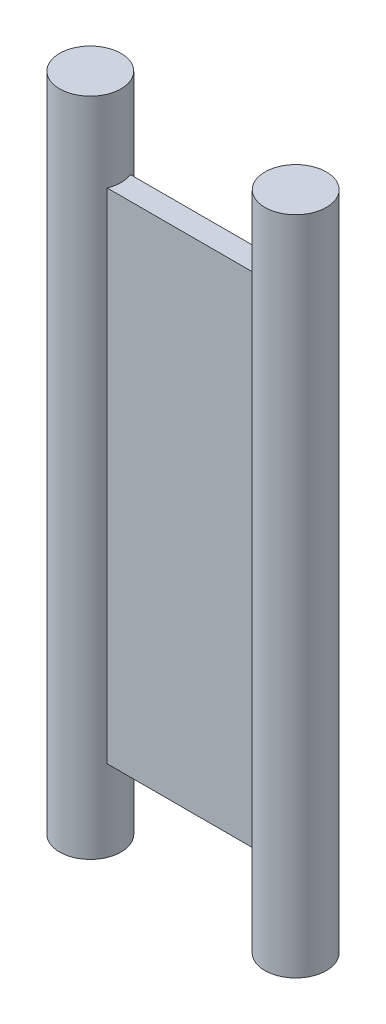
SolidWorks part; units mm, degrees
ref_plane "Front Plane" through (0, 0, 0) normal (0, 0, 1) x (1, 0, 0)
ref_plane "Top Plane" through (0, 0, 0) normal (0, 1, 0) x (1, 0, 0)
ref_plane "Right Plane" through (0, 0, 0) normal (1, 0, 0) x (0, 0, -1)
sketch "Sketch1" plane through (0, 0, 0) normal (0, 1, 0) x (1, 0, 0)
  line L1 (4.427, 0.5) -> (-4.427, 0.5)
  line L2 (4.427, 0.5) -> (4.427, -0.5)
  line L3 (4.427, -0.5) -> (-4.427, -0.5)
  line L4 (-4.427, 0.5) -> (-4.427, -0.5)
  line L5 (4.427, 0.5) -> (-4.427, -0.5) construction
  line L6 (4.427, -0.5) -> (-4.427, 0.5) construction
  point P0 (0, 0)
  dimension "D1" = 8.854
  dimension "D3" = 1
extrude "Boss-Extrude1" add sketch "Sketch1" along normal blind 21.5
ref_plane "Plane1" through (0, 10.75, 0) normal (0, 1, 0) x (1, 0, 0)
sketch "Sketch2" plane through (0, 10.75, 0) normal (0, 1, 0) x (1, 0, 0)
  line L0 (4.427, -0.5) -> (4.427, 0.5) construction
  line L1 (-4.427, 0.5) -> (-4.427, -0.5) construction
  line L2 (4.427, -0.5) -> (4.427, 0.5) construction
  line L3 (-4.427, 0.5) -> (-4.427, -0.5) construction
  circle A0 centre (-4.427, 0) radius 1.325
  circle A1 centre (4.427, 0) radius 1.325
  dimension "D1" = 2.65
extrude "Boss-Extrude2" add sketch "Sketch2" along normal mid plane 28.5
